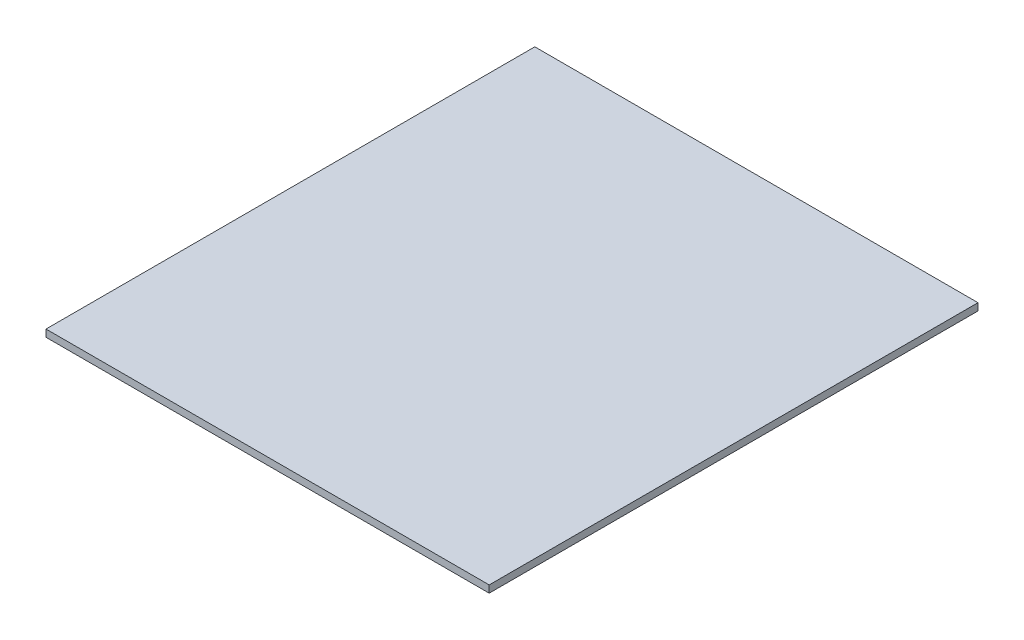
SolidWorks part; units mm, degrees
ref_plane "Front Plane" through (0, 0, 0) normal (0, 0, 1) x (1, 0, 0)
ref_plane "Top Plane" through (0, 0, 0) normal (0, 1, 0) x (1, 0, 0)
ref_plane "Right Plane" through (0, 0, 0) normal (1, 0, 0) x (0, 0, -1)
sketch "Sketch4" plane through (0, 0, 0) normal (0, 1, 0) x (1, 0, 0)
  line L5 (-340, -375) -> (340, -375)
  line L6 (-340, -375) -> (-340, 375)
  line L7 (-340, 375) -> (340, 375)
  line L8 (340, -375) -> (340, 375)
  line L9 (-340, -375) -> (340, 375) construction
  line L10 (-340, 375) -> (340, -375) construction
  point P0 (0, 0)
  dimension "D1" = 680
  dimension "D2" = 750
extrude "Boss-Extrude1" add sketch "Sketch4" along normal blind 11
sketch "Sketch5" plane through (0, 0, 0) normal (0, 1, 0) x (1, 0, 0)
  line L0 (0, 375) -> (0, -375) construction
  line L2 (340, 375) -> (-340, 375) construction
  line L4 (-340, -375) -> (340, -375) construction
  line L5 (340, 0) -> (-340, 0) construction
  line L6 (340, -375) -> (340, 375) construction
  line L7 (-340, 375) -> (-340, -375) construction
  line L8 (290, 375) -> (290, 225)
  line L9 (-290, 375) -> (-60, 375)
  line L10 (-290, 375) -> (-290, 225)
  line L11 (-290, 225) -> (-60, 225)
  line L12 (-60, 375) -> (-60, 225)
  line L13 (290, 225) -> (60, 225)
  line L14 (60, 375) -> (60, 225)
  line L15 (60, -375) -> (60, -225)
  line L16 (290, -375) -> (290, -225)
  line L17 (290, -225) -> (60, -225)
  line L18 (-60, -375) -> (-60, -225)
  line L19 (-290, -375) -> (-290, -225)
  line L20 (-290, -225) -> (-60, -225)
  line L21 (-318, 300) -> (-318, 375) construction
  line L22 (-318, 300) -> (-290, 300) construction
  line L23 (-318, 300) -> (-32, 300) construction
  line L24 (-290, -375) -> (-60, -375)
  line L25 (290, -375) -> (60, -375)
  line L26 (290, 375) -> (60, 375)
  circle A0 centre (-318, 300) radius 9
  circle A1 centre (-32, 300) radius 9
  dimension "D5" = 18
  dimension "D8" = 18
  dimension "D1" = 150
  dimension "D2" = 230
  dimension "D3" = 50
  dimension "D4" = 75
  dimension "D6" = 28
  dimension "D7" = 286
